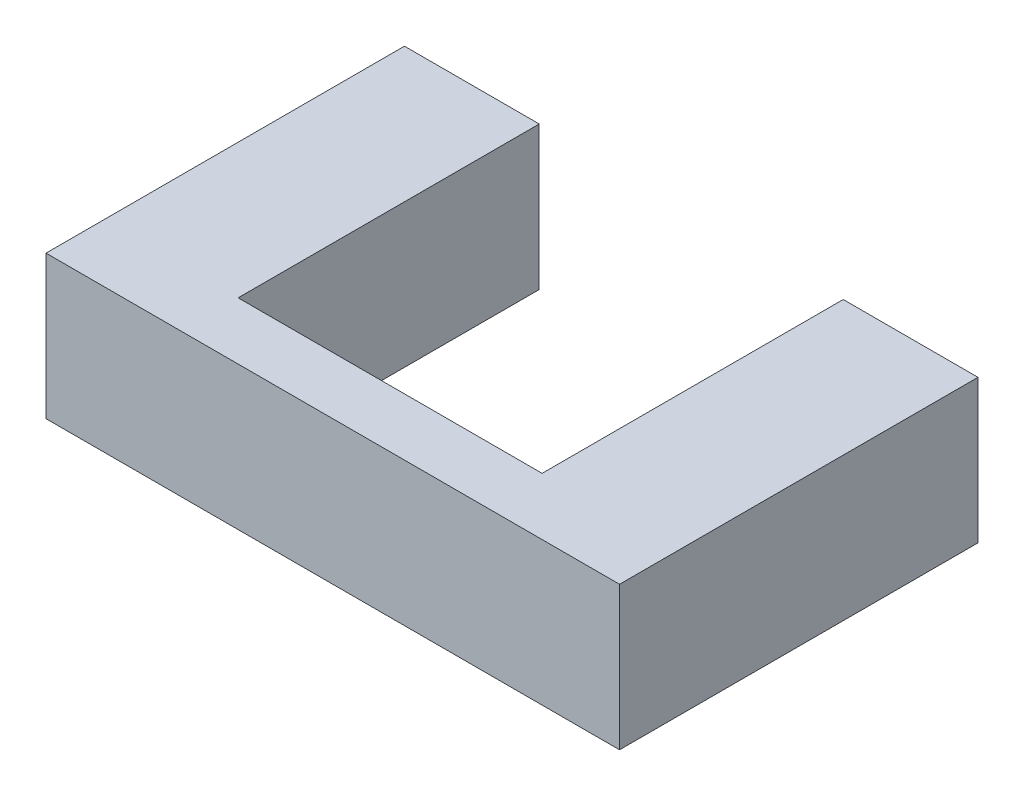
SolidWorks part; units mm, degrees
ref_plane "Front Plane" through (0, 0, 0) normal (0, 0, 1) x (1, 0, 0)
ref_plane "Top Plane" through (0, 0, 0) normal (0, 1, 0) x (1, 0, 0)
ref_plane "Right Plane" through (0, 0, 0) normal (1, 0, 0) x (0, 0, -1)
sketch "Sketch1" plane through (0, 0, 0) normal (0, 1, 0) x (1, 0, 0)
  line L1 (-25.4, 15.875) -> (25.4, 15.875)
  line L2 (-25.4, 15.875) -> (-25.4, -15.875)
  line L3 (-25.4, -15.875) -> (25.4, -15.875)
  line L4 (25.4, 15.875) -> (25.4, -15.875)
  line L5 (-25.4, 15.875) -> (25.4, -15.875) construction
  line L6 (-25.4, -15.875) -> (25.4, 15.875) construction
  point P0 (0, 0)
  dimension "D1" = 31.75
  dimension "D2" = 50.8
extrude "Boss-Extrude1" add sketch "Sketch1" along normal blind 12.7
sketch "Sketch2" plane through (0, 12.7, 0) normal (0, 1, 0) x (1, 0, 0)
  line L0 (25.4, 15.875) -> (-25.4, 15.875) construction
  line L1 (13.462, 15.875) -> (-13.462, 15.875)
  line L2 (13.462, 15.875) -> (13.462, -10.795)
  line L3 (13.462, -10.795) -> (-13.462, -10.795)
  line L4 (-13.462, 15.875) -> (-13.462, -10.795)
  line L5 (25.4, -15.875) -> (25.4, 15.875) construction
  dimension "D1" = 26.924
  dimension "D2" = 26.67
  dimension "D3" = 11.938
extrude "Cut-Extrude1" cut sketch "Sketch2" against normal blind 12.7
